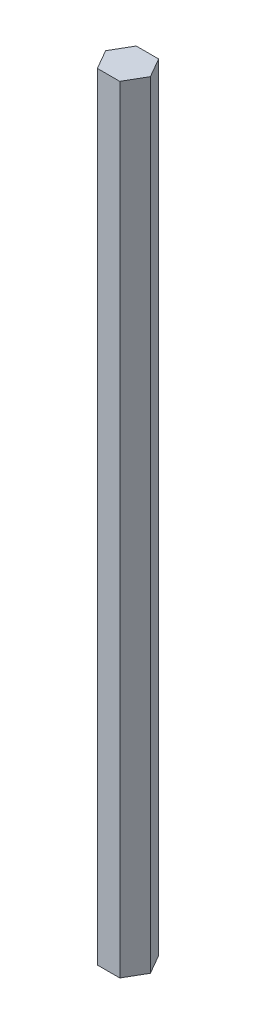
SolidWorks part; units mm, degrees
ref_plane "Front Plane" through (0, 0, 0) normal (0, 0, 1) x (1, 0, 0)
ref_plane "Top Plane" through (0, 0, 0) normal (0, 1, 0) x (1, 0, 0)
ref_plane "Right Plane" through (0, 0, 0) normal (1, 0, 0) x (0, 0, -1)
sketch "Sketch1" plane through (0, 0, 0) normal (0, 1, 0) x (1, 0, 0)
  line L1 (7.3323, 0) -> (3.6662, 6.35)
  line L2 (3.6662, 6.35) -> (-3.6662, 6.35)
  line L3 (-3.6662, 6.35) -> (-7.3323, 0)
  line L4 (-7.3323, 0) -> (-3.6662, -6.35)
  line L5 (-3.6662, -6.35) -> (3.6662, -6.35)
  line L6 (3.6662, -6.35) -> (7.3323, 0)
  circle A0 centre (0, 0) radius 6.35 construction
  point P1 (0, 0)
extrude "Boss-Extrude1" add sketch "Sketch1" along normal blind 254 contours L2 L3 L4 L5 L6 L1
